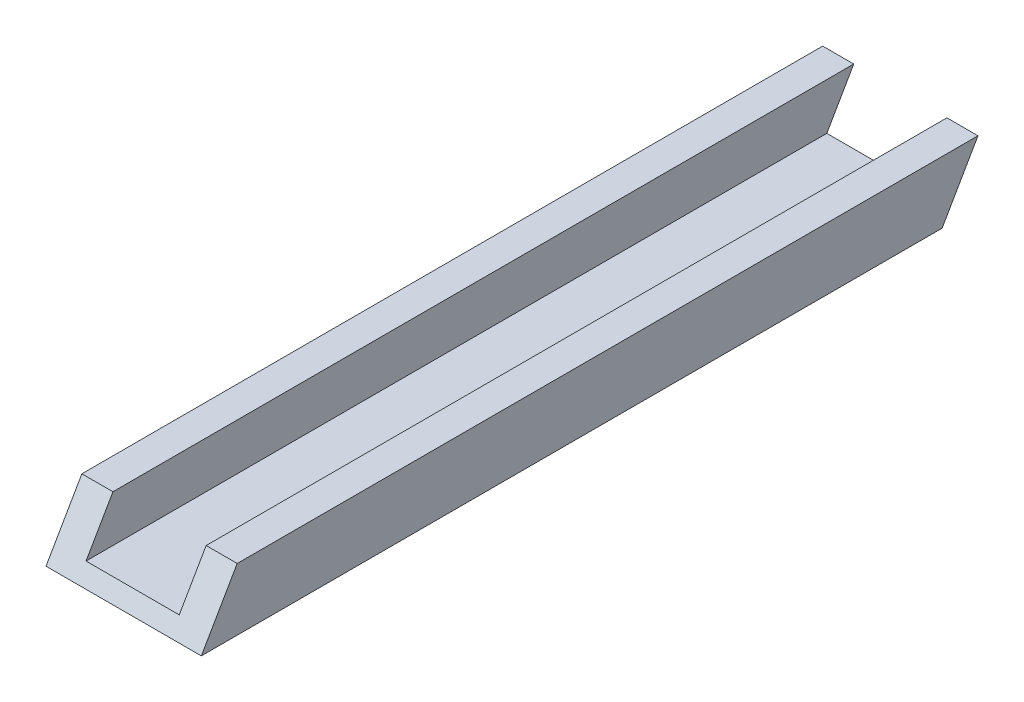
SolidWorks part; units mm, degrees
ref_plane "Front Plane" through (0, 0, 0) normal (0, 0, 1) x (1, 0, 0)
ref_plane "Top Plane" through (0, 0, 0) normal (0, 1, 0) x (1, 0, 0)
ref_plane "Right Plane" through (0, 0, 0) normal (1, 0, 0) x (0, 0, -1)
sketch "Sketch2" plane through (0, 0, 0) normal (0, 1, 0) x (1, 0, 0)
  line L1 (0, 0) -> (50, 0)
  line L2 (0, 0) -> (0, 250)
  line L3 (0, 250) -> (50, 250)
  line L4 (50, 0) -> (50, 250)
  dimension "D1" = 50
  dimension "D2" = 250
extrude "Boss-Extrude1" add sketch "Sketch2" along normal blind 20
sketch "Sketch3" plane through (50, 0, 0) normal (1, 0, 0) x (0, 0, -1)
  line L0 (0, 0) -> (11.547, 20)
  line L1 (0, 20) -> (250, 20) construction
  line L2 (11.547, 20) -> (250, 20)
  line L3 (250, 20) -> (238.453, 0)
  line L4 (0, 0) -> (250, 0) construction
  line L5 (238.453, 0) -> (0, 0)
  dimension "D1" = 60
extrude "Cut-Extrude1" cut sketch "Sketch3" against normal through all both and the other way through all flip side to cut
sketch "Sketch4" plane through (50, 0, 0) normal (1, 0, 0) x (0, 0, -1)
  line L0 (11.547, 20) -> (250, 20)
  line L1 (250, 20) -> (241.3397, 5)
  line L2 (250, 20) -> (238.453, 0) construction
  line L3 (241.3397, 5) -> (2.8868, 5)
  line L4 (0, 0) -> (11.547, 20) construction
  line L5 (2.8868, 5) -> (11.547, 20)
  line L6 (0, 0) -> (238.453, 0) construction
  dimension "D1" = 5
extrude "Cut-Extrude2" cut sketch "Sketch4" against normal blind 30 from offset 10
